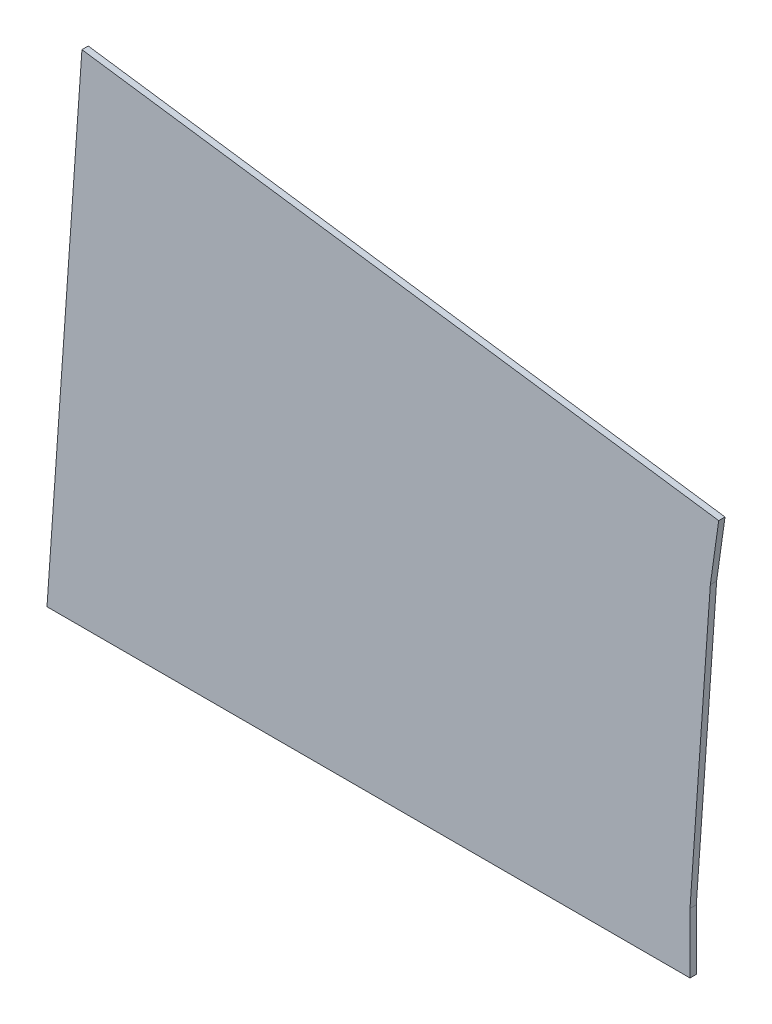
SolidWorks part; units mm, degrees
ref_plane "Front Plane" through (0, 0, 0) normal (0, 0, 1) x (1, 0, 0)
ref_plane "Top Plane" through (0, 0, 0) normal (0, 1, 0) x (1, 0, 0)
ref_plane "Right Plane" through (0, 0, 0) normal (1, 0, 0) x (0, 0, -1)
sketch "Sketch1" plane through (0, 0, 0) normal (0, 0, 1) x (1, 0, 0)
  line L0 (100, -9.525) -> (100, 9.525)
  line L1 (100, 9.525) -> (106.4244, 101.3981)
  line L2 (106.4244, 101.3981) -> (109.0756, 120.2627)
  line L3 (109.0756, 120.2627) -> (-92.2825, 148.5617)
  line L4 (-92.2825, 148.5617) -> (-103.337, -9.525)
  line L5 (-103.337, -9.525) -> (100, -9.525)
  line L6 (-103.3208, -9.2928) -> (-92.2987, 148.3295) construction
extrude "Boss-Extrude1" add sketch "Sketch1" along normal blind 2
